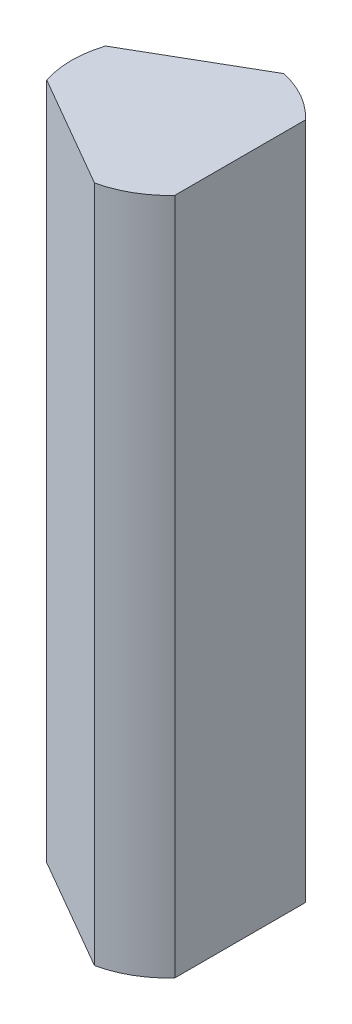
SolidWorks part; units mm, degrees
material "201 Aço inoxidável recozido (SS)"
ref_plane "Plano frontal" through (0, 0, 0) normal (0, 0, 1) x (1, 0, 0)
ref_plane "Plano superior" through (0, 0, 0) normal (0, 1, 0) x (1, 0, 0)
ref_plane "Plano direito" through (0, 0, 0) normal (1, 0, 0) x (0, 0, -1)
sketch "Esboço1" plane through (0, 0, 0) normal (0, 1, 0) x (1, 0, 0)
  line L0 (0.4916, -2.2468) -> (-2.1916, -0.6976)
  line L1 (-2.1916, 0.6976) -> (0.4916, 2.2468)
  line L2 (1.7, -1.5492) -> (1.7, 1.5492)
  line L3 (1.15, -1.9919) -> (-0.85, 1.4722) construction
  line L4 (-2.3, 0) -> (1.7, 0) construction
  arc A0 (0.4916, -2.2468) -> (1.7, -1.5492) centre (0, 0) ccw
  arc A1 (1.7, 1.5492) -> (0.4916, 2.2468) centre (0, 0) ccw
  arc A2 (-2.1916, -0.6976) -> (-2.1916, 0.6976) centre (0, 0) cw
  dimension "D1" = 2.3
  dimension "D2" = 4
extrude "Ressalto-extrusão1" add sketch "Esboço1" along normal blind 16.0875
